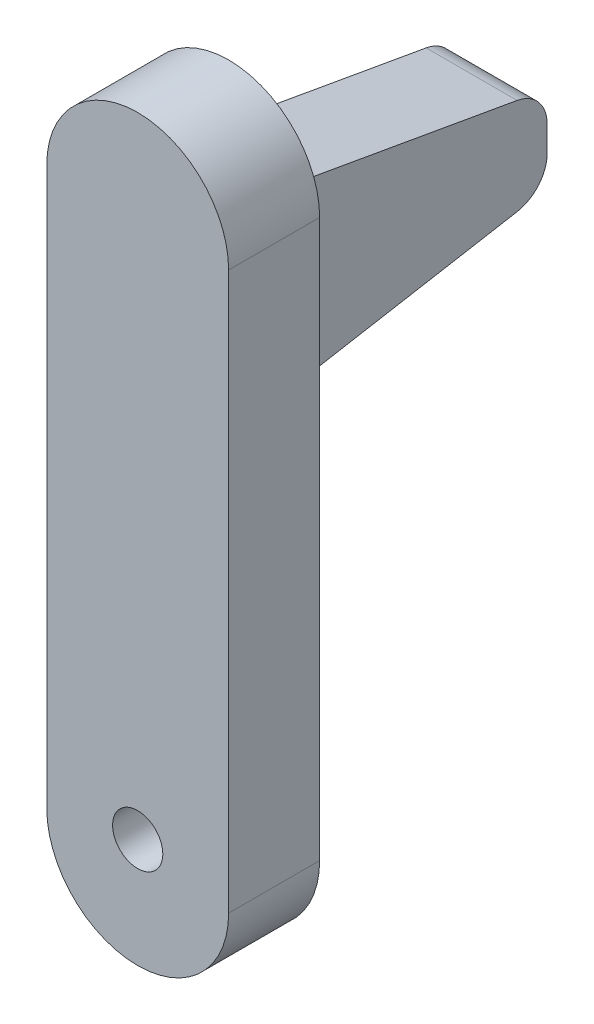
SolidWorks part; units mm, degrees
ref_plane "Front Plane" through (0, 0, 0) normal (0, 0, 1) x (1, 0, 0)
ref_plane "Top Plane" through (0, 0, 0) normal (0, 1, 0) x (1, 0, 0)
ref_plane "Right Plane" through (0, 0, 0) normal (1, 0, 0) x (0, 0, -1)
sketch "Sketch1" plane through (0, 0, 0) normal (0, 0, 1) x (1, 0, 0)
  line L3 (-6.345, -1.27) -> (-6.345, 37.592)
  line L4 (6.345, 37.592) -> (6.345, -1.27)
  circle A0 centre (0, 0) radius 1.7526
  arc A1 (6.345, 37.592) -> (-6.345, 37.592) centre (0, 37.592) ccw
  arc A2 (6.345, -1.27) -> (-6.345, -1.27) centre (0, -1.27) cw
extrude "Boss-Extrude1" add sketch "Sketch1" along normal blind 6.35
sketch "Sketch2" plane through (0, 0, 0) normal (1, 0, 0) x (0, 0, -1)
  line L0 (0, 37.592) -> (0, 24.892)
  line L1 (0, -1.27) -> (0, 37.592) construction
  line L5 (19.05, 30.3823) -> (19.05, 32.1017)
  line L6 (16.9511, 34.6031) -> (0, 37.592)
  line L7 (16.9511, 27.8809) -> (0, 24.892)
  arc A0 (16.9511, 27.8809) -> (19.05, 30.3823) centre (16.51, 30.3823) ccw
  arc A1 (19.05, 32.1017) -> (16.9511, 34.6031) centre (16.51, 32.1017) ccw
  dimension "D1" = 2.54
extrude "Boss-Extrude2" add sketch "Sketch2" along normal blind 3.175 and the other way blind 3.175
